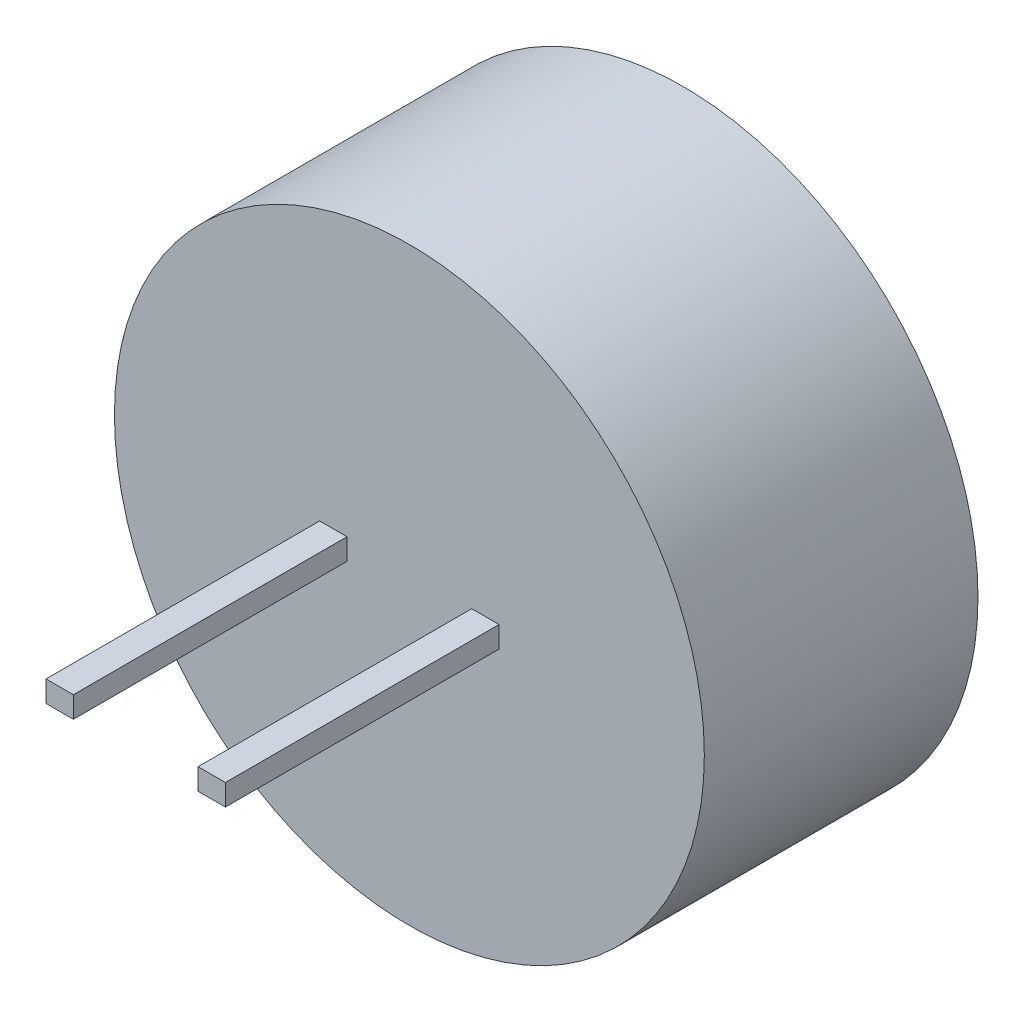
SolidWorks part; units mm, degrees
ref_plane "Front Plane" through (0, 0, 0) normal (0, 0, 1) x (1, 0, 0)
ref_plane "Top Plane" through (0, 0, 0) normal (0, 1, 0) x (1, 0, 0)
ref_plane "Right Plane" through (0, 0, 0) normal (1, 0, 0) x (0, 0, -1)
sketch "Sketch2" plane through (0, 0, 0) normal (0, 0, 1) x (1, 0, 0)
  circle A0 centre (0, 0) radius 4.85
  dimension "D1" = 9.7
extrude "Boss-Extrude1" add sketch "Sketch2" along normal blind 4.5
sketch "Sketch3" plane through (0, 0, 4.5) normal (0, 0, 1) x (1, 0, 0)
  line L0 (0, 4.85) -> (0, -4.85) construction
  line L1 (-1.475, 0.175) -> (-1.025, 0.175)
  line L2 (-1.475, 0.175) -> (-1.475, -0.175)
  line L3 (-1.475, -0.175) -> (-1.025, -0.175)
  line L4 (-1.025, 0.175) -> (-1.025, -0.175)
  line L5 (-1.475, 0.175) -> (-1.025, -0.175) construction
  line L6 (-1.475, -0.175) -> (-1.025, 0.175) construction
  line L7 (1.475, 0.175) -> (1.475, -0.175)
  line L8 (1.475, -0.175) -> (1.025, -0.175)
  line L9 (1.025, 0.175) -> (1.025, -0.175)
  line L10 (1.475, 0.175) -> (1.025, 0.175)
  circle A0 centre (0, 0) radius 4.85 construction
  point P0 (-1.25, 0)
  dimension "D1" = 1.25
  dimension "D2" = 0.45
  dimension "D3" = 0.35
extrude "Boss-Extrude2" add sketch "Sketch3" along normal blind 4.5
